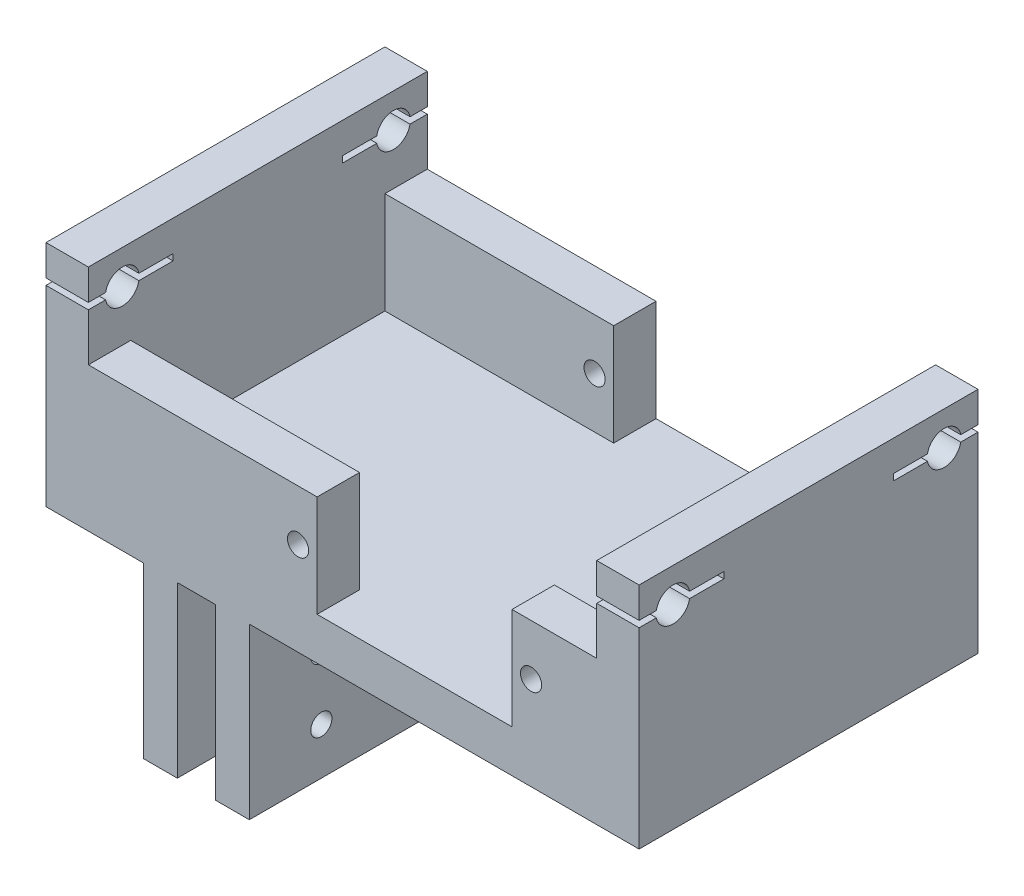
SolidWorks part; units mm, degrees
ref_plane "Front Plane" through (0, 0, 0) normal (0, 0, 1) x (1, 0, 0)
ref_plane "Top Plane" through (0, 0, 0) normal (0, 1, 0) x (1, 0, 0)
ref_plane "Right Plane" through (0, 0, 0) normal (1, 0, 0) x (0, 0, -1)
sketch "Sketch1" plane through (0, 0, 0) normal (0, 1, 0) x (1, 0, 0)
  line L1 (-35, -20) -> (35, -20)
  line L2 (-35, -20) -> (-35, 20)
  line L3 (-35, 20) -> (35, 20)
  line L4 (35, -20) -> (35, 20)
  line L5 (-35, -20) -> (35, 20) construction
  line L6 (-35, 20) -> (35, -20) construction
  point P0 (0, 0)
  dimension "D1" = 70
  dimension "D2" = 40
extrude "Boss-Extrude1" add sketch "Sketch1" along normal blind 5
sketch "Sketch2" plane through (0, 5, 0) normal (0, 1, 0) x (1, 0, 0)
  line L0 (-3, -20) -> (-3, -15)
  line L1 (-35, -20) -> (35, -20) construction
  line L2 (-3, -15) -> (-30, -15)
  line L3 (-35, 20) -> (-35, -20) construction
  line L4 (-30, -15) -> (-30, 15)
  line L6 (-30, 15) -> (-3, 15)
  line L7 (-3, 15) -> (-3, 20)
  line L8 (35, 20) -> (-35, 20) construction
  line L9 (-3, 20) -> (-35, 20)
  line L10 (-35, 20) -> (-35, -20)
  line L11 (-35, -20) -> (-3, -20)
  line L12 (20, -15) -> (30, -15)
  line L13 (35, -20) -> (35, 20) construction
  line L14 (30, -15) -> (30, 15)
  line L15 (30, 15) -> (20, 15)
  line L16 (20, 15) -> (20, 20)
  line L17 (20, 20) -> (35, 20)
  line L18 (35, 20) -> (35, -20)
  line L19 (35, -20) -> (20, -20)
  line L20 (20, -20) -> (20, -15)
  dimension "D1" = 32
  dimension "D2" = 5
  dimension "D3" = 30
  dimension "D4" = 5
  dimension "D5" = 5
  dimension "D6" = 15
  dimension "D9" = 5
extrude "Boss-Extrude2" add sketch "Sketch2" along normal blind 12
sketch "Sketch3" plane through (0, 17, 0) normal (0, 1, 0) x (1, 0, 0)
  line L0 (35, 20) -> (20, 20) construction
  line L1 (35, -20) -> (30, -20)
  line L2 (35, -20) -> (35, 20)
  line L3 (35, 20) -> (30, 20)
  line L4 (30, -20) -> (30, 20)
  line L5 (30, 15) -> (30, -15) construction
  line L6 (-35, -20) -> (-3, -20) construction
  line L7 (-35, 20) -> (-30, 20)
  line L8 (-35, 20) -> (-35, -20)
  line L9 (-35, -20) -> (-30, -20)
  line L10 (-30, 20) -> (-30, -20)
  line L11 (-30, -15) -> (-30, 15) construction
extrude "Boss-Extrude3" add sketch "Sketch3" along normal blind 10
sketch "Sketch5" plane through (-35, 0, 0) normal (-1, 0, 0) x (0, 0, 1)
  line L0 (-20, 27) -> (20, 27) construction
  line L1 (20, 27) -> (20, 0) construction
  line L2 (0, -2.75) -> (0, 2.75) construction
  circle A0 centre (16, 23) radius 2
  circle A1 centre (-16, 23) radius 2
  dimension "D1" = 4
  dimension "D2" = 4
  dimension "D3" = 4
extrude "Cut-Extrude1" cut sketch "Sketch5" against normal through all
sketch "Sketch7" plane through (0, 0, 15) normal (0, 0, -1) x (-1, 0, 0)
  line L0 (-20, 17) -> (-20, 5) construction
  line L1 (3, 17) -> (3, 5) construction
  line L2 (3, 17) -> (30, 17) construction
  line L3 (-30, 17) -> (-20, 17) construction
  circle A0 centre (-22.25, 11) radius 1.25
  circle A1 centre (5.25, 11) radius 1.25
  dimension "D1" = 2.5
  dimension "D2" = 2.25
  dimension "D4" = 6
  dimension "D5" = 2.5
  dimension "D6" = 6
  dimension "D3" = 2.25
extrude "Cut-Extrude3" cut sketch "Sketch7" against normal through all and the other way through all
sketch "Sketch8" plane through (-35, 0, 0) normal (-1, 0, 0) x (0, 0, 1)
  line L0 (20, 27) -> (20, 0) construction
  line L1 (20, 23.375) -> (10, 23.375)
  line L2 (20, 23.375) -> (20, 22.625)
  line L3 (20, 22.625) -> (10, 22.625)
  line L4 (-20, 23.375) -> (-20, 22.625)
  line L5 (-20, 27) -> (-20, 0) construction
  line L6 (10, 23.375) -> (10, 22.625)
  line L7 (-10, 23.375) -> (-10, 22.625)
  line L8 (-10, 23.375) -> (-20, 23.375)
  line L9 (-10, 22.625) -> (-20, 22.625)
  circle A0 centre (16, 23) radius 2 construction
  dimension "D1" = 0.75
  dimension "D2" = 0.375
  dimension "D3" = 10
  dimension "D4" = 10
extrude "Cut-Extrude4" cut sketch "Sketch8" against normal through all
sketch "Sketch9" plane through (0, 0, 0) normal (0, -1, 0) x (-1, 0, 0)
  line L0 (35, -20) -> (-35, -20) construction
  line L1 (23.5, -20) -> (19.5, -20)
  line L2 (23.5, -20) -> (23.5, 20)
  line L3 (23.5, 20) -> (19.5, 20)
  line L4 (19.5, -20) -> (19.5, 20)
  line L5 (-35, 20) -> (35, 20) construction
  line L6 (0, -20) -> (0, 19.3326) construction
  line L7 (15, -20) -> (11, -20)
  line L8 (15, -20) -> (15, 20)
  line L9 (15, 20) -> (11, 20)
  line L10 (11, -20) -> (11, 20)
  dimension "D1" = 4
  dimension "D2" = 4
  dimension "D3" = 4.5
  dimension "D4" = 15
extrude "Boss-Extrude4" add sketch "Sketch9" along normal blind 20
sketch "Sketch11" plane through (-1.6583, 0, 0) normal (-1, 0, 0) x (0, 0, 1)
  circle A1 centre (11.5, -14.5) radius 1.25
  circle A2 centre (-16, -14.5) radius 1.25
  circle A3 centre (-16, -7) radius 1.25
  circle A4 centre (11.5, -7) radius 1.25
  dimension "D1" = 2.5
  dimension "D2" = 2.5
  dimension "D3" = 2.5
  dimension "D4" = 7.5
  dimension "D5" = 2.5
  dimension "D6" = 7.5
  dimension "D7" = 27.5
extrude "Cut-Extrude5" cut sketch "Sketch11" against normal through all and the other way through all
